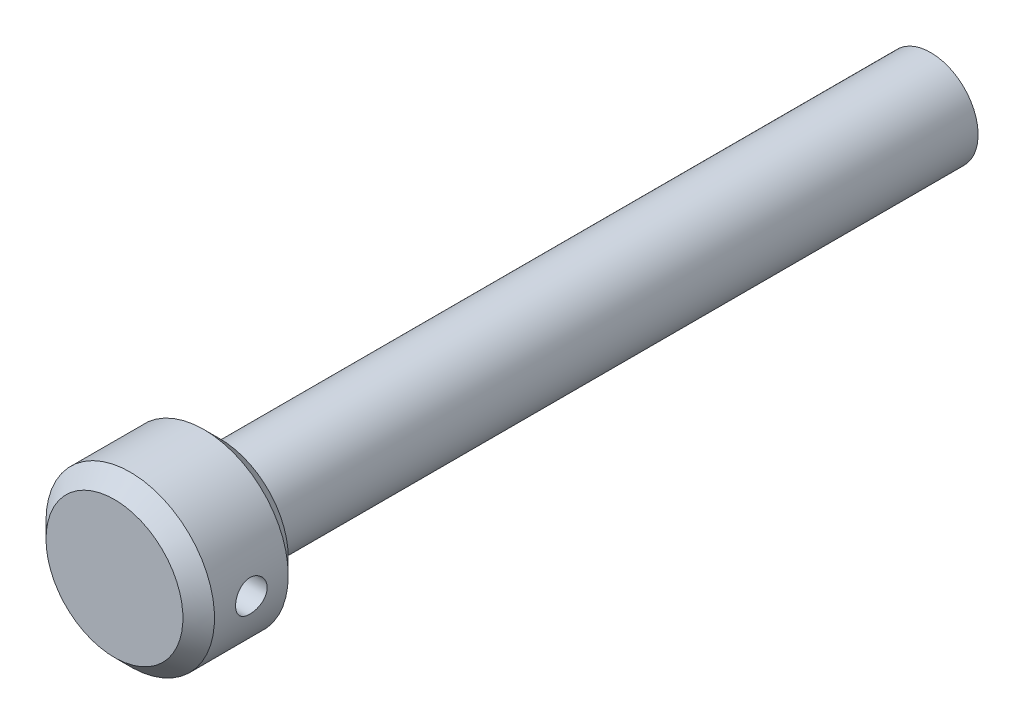
SolidWorks part; units mm, degrees
ref_plane "Ön Düzlem" through (0, 0, 0) normal (0, 0, 1) x (1, 0, 0)
ref_plane "Üst Düzlem" through (0, 0, 0) normal (0, 1, 0) x (1, 0, 0)
ref_plane "Sağ Düzlem" through (0, 0, 0) normal (1, 0, 0) x (0, 0, -1)
sketch "Çizim1" plane through (0, 0, 0) normal (0, 0, 1) x (1, 0, 0)
  circle A0 centre (-35.6875, 19.9803) radius 16
  dimension "D1" = 32
extrude "Yükseklik-Ekstrüzyon1" add sketch "Çizim1" along normal blind 20
chamfer "Pah2" distance 3 angle 45 1 edges at (-19.6875, 19.9803, 20)
chamfer "Pah3" distance 3 angle 45 1 edges at (-19.6875, 19.9803, 0)
sketch "Çizim2" plane through (0, 0, 0) normal (0, 0, -1) x (-1, 0, 0)
  circle A0 centre (35.6875, 19.9803) radius 9
  dimension "D1" = 18
extrude "Yükseklik-Ekstrüzyon2" add sketch "Çizim2" along normal blind 135
sketch "Çizim3" plane through (0, 0, 0) normal (1, 0, 0) x (0, 0, -1)
  line L0 (-17, 3.9803) -> (-3, 3.9803) construction
  line L1 (-20, 32.9803) -> (-20, 6.9803) construction
  circle A0 centre (-10, 19.9803) radius 3
  dimension "D1" = 6
  dimension "D2" = 16
  dimension "D3" = 10
extrude "Kes-Ekstrüzyon1" cut sketch "Çizim3" against normal through all
